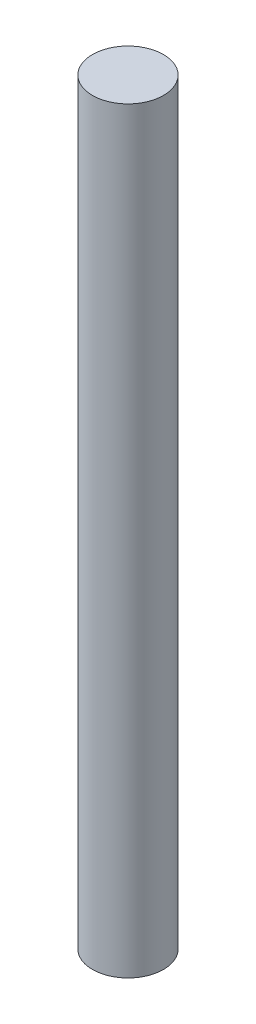
SolidWorks part; units mm, degrees
ref_plane "Front Plane" through (0, 0, 0) normal (0, 0, 1) x (1, 0, 0)
ref_plane "Top Plane" through (0, 0, 0) normal (0, 1, 0) x (1, 0, 0)
ref_plane "Right Plane" through (0, 0, 0) normal (1, 0, 0) x (0, 0, -1)
sketch "Sketch1" plane through (0, 0, 0) normal (0, 1, 0) x (1, 0, 0)
  circle A0 centre (0, 0) radius 1.5
  dimension "D1" = 3
extrude "Boss-Extrude1" add sketch "Sketch1" along normal blind 32
